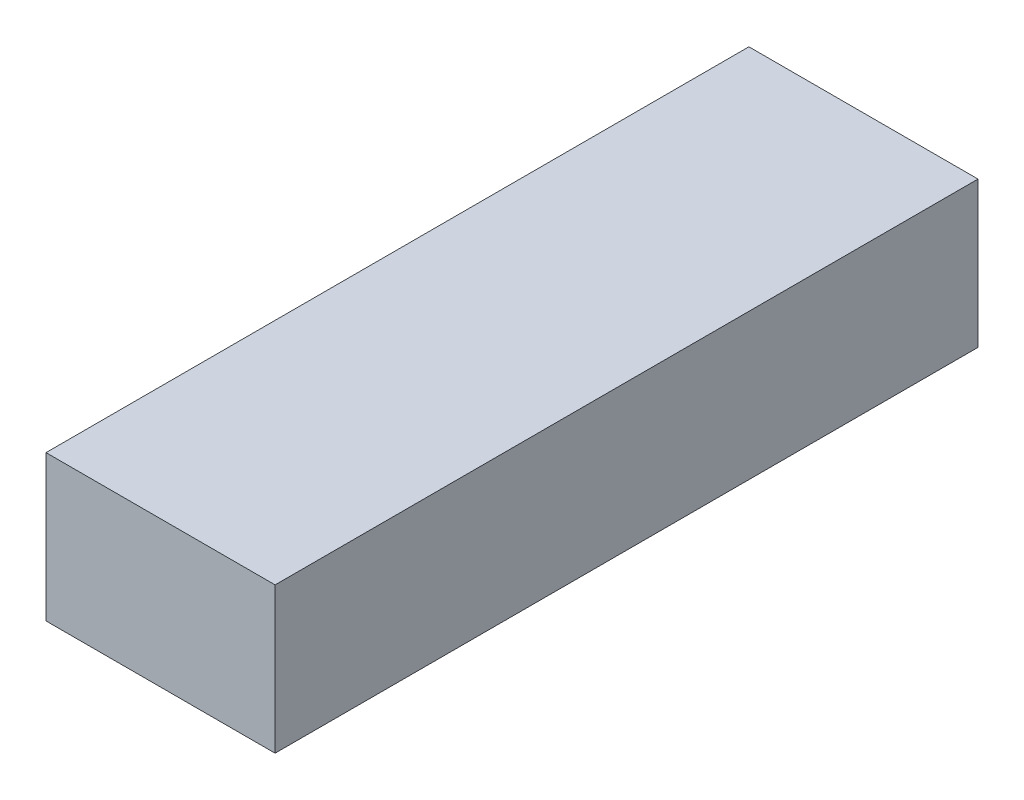
SolidWorks part; units mm, degrees
ref_plane "Front Plane" through (0, 0, 0) normal (0, 0, 1) x (1, 0, 0)
ref_plane "Top Plane" through (0, 0, 0) normal (0, 1, 0) x (1, 0, 0)
ref_plane "Right Plane" through (0, 0, 0) normal (1, 0, 0) x (0, 0, -1)
sketch "Sketch1" plane through (0, 0, 0) normal (0, 1, 0) x (1, 0, 0)
  line L1 (0, 0) -> (44, 0)
  line L2 (0, 0) -> (0, 135)
  line L3 (0, 135) -> (44, 135)
  line L4 (44, 0) -> (44, 135)
  dimension "D1" = 135
  dimension "D2" = 44
extrude "Boss-Extrude1" add sketch "Sketch1" along normal blind 28
